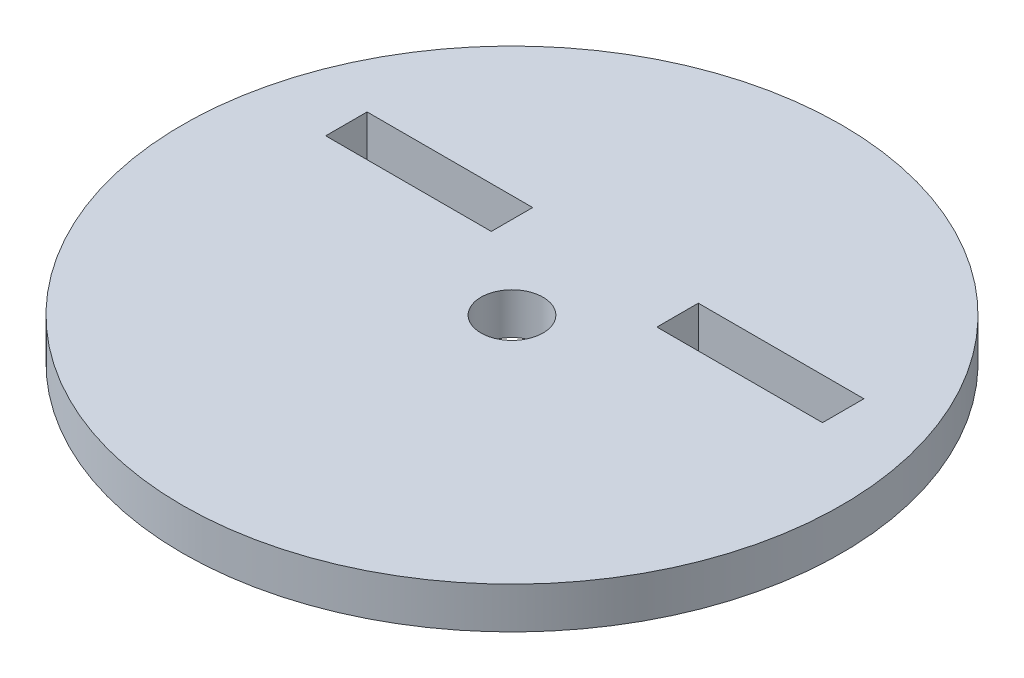
SolidWorks part; units mm, degrees
material "Maple"
ref_plane "Front Plane" through (0, 0, 0) normal (0, 0, 1) x (1, 0, 0)
ref_plane "Top Plane" through (0, 0, 0) normal (0, 1, 0) x (1, 0, 0)
ref_plane "Right Plane" through (0, 0, 0) normal (1, 0, 0) x (0, 0, -1)
sketch "Sketch1" plane through (0, 0, 0) normal (0, 1, 0) x (1, 0, 0)
  line L0 (-48.9245, 12.7) -> (48.9245, 12.7) construction
  line L1 (0, -50.546) -> (0, 50.546) construction
  line L2 (-38.1, 15.875) -> (-12.7, 15.875)
  line L3 (-38.1, 15.875) -> (-38.1, 9.525)
  line L4 (-38.1, 9.525) -> (-12.7, 9.525)
  line L5 (-12.7, 15.875) -> (-12.7, 9.525)
  line L6 (-38.1, 15.875) -> (-12.7, 9.525) construction
  line L7 (-38.1, 9.525) -> (-12.7, 15.875) construction
  line L8 (12.7, 15.875) -> (12.7, 9.525)
  line L9 (38.1, 9.525) -> (12.7, 9.525)
  line L10 (38.1, 15.875) -> (38.1, 9.525)
  line L11 (38.1, 15.875) -> (12.7, 15.875)
  circle A0 centre (0, 0) radius 4.7625
  circle A1 centre (0, 0) radius 50.546
  circle A2 centre (0, 0) radius 3.175 construction
  point P7 (-25.4, 12.7)
  point P14 (0, 0)
  dimension "D1" = 101.092
  dimension "D2" = 6.35
  dimension "D3" = 9.525
  dimension "D4" = 6.35
  dimension "D5" = 25.4
  dimension "D6" = 25.4
  dimension "D7" = 12.7
extrude "Boss-Extrude1" add sketch "Sketch1" along normal blind 6.35
